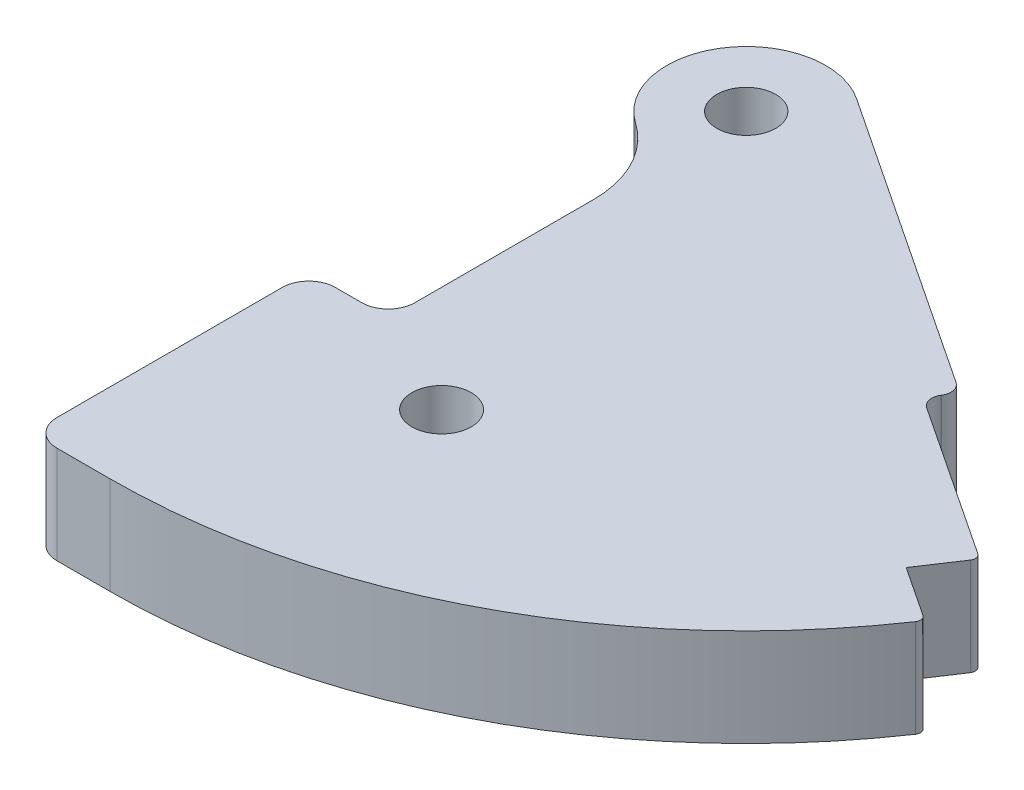
SolidWorks part; units mm, degrees
ref_plane "Front Plane" through (0, 0, 0) normal (0, 0, 1) x (1, 0, 0)
ref_plane "Top Plane" through (0, 0, 0) normal (0, 1, 0) x (1, 0, 0)
ref_plane "Right Plane" through (0, 0, 0) normal (1, 0, 0) x (0, 0, -1)
sketch "Sketch1" plane through (0, 0, 0) normal (0, 1, 0) x (1, 0, 0)
  line L0 (0, -4.7625) -> (0, -21.4312)
  line L1 (0, 0) -> (31.75, -21.0606) construction
  line L2 (0, 0) -> (31.75, 0) construction
  line L3 (31.75, 0) -> (31.75, -38.2189) construction
  line L4 (2.6326, 3.9688) -> (20.9847, -8.2046)
  line L5 (-4.7625, 0) -> (-4.7625, -37.8012) construction
  line L6 (0, -21.4312) -> (-4.7625, -21.4312)
  line L7 (-4.7625, -21.4312) -> (-4.7625, -38.1)
  line L8 (0, -38.1) -> (-4.7625, -38.1)
  line L9 (28.4427, -18.8668) -> (30.1978, -16.2209)
  line L10 (20.9847, -8.2046) -> (20.1309, -9.5433)
  line L11 (28.4427, -18.8668) -> (31.75, -21.0606)
  line L12 (30.1978, -16.2209) -> (20.1309, -9.5433)
  arc A0 (0, -38.1) -> (31.75, -21.0606) centre (0, 0) ccw
  circle A1 centre (0, 0) radius 1.7653
  arc A2 (4.7625, 0) -> (0, -4.7625) centre (0, 0) ccw
  arc A3 (4.7625, 0) -> (0, -4.7625) centre (0, 0) cw
  circle A4 centre (6.35, -24.5934) radius 1.778
  dimension "D2" = 76.2
  dimension "D3" = 3.5306
  dimension "D4" = 9.525
  dimension "D9" = 3.556
  dimension "D1" = 31.75
  dimension "D5" = 16.6687
  dimension "D6" = 16.6688
  dimension "D7" = 3.9688
  dimension "D10" = 6.35
  dimension "D11" = 25.4
  dimension "D12" = 3.175
extrude "Boss-Extrude1" add sketch "Sketch1" along normal blind 5.842
fillet "Fillet3" radius 1.5875 3 edges at (-4.7625, 2.921, 38.1) (-4.7625, 2.921, 21.4312) (0, 2.921, 21.4312)
fillet "Fillet6" radius 6.35 1 edges at (0, 2.921, 4.7625)
fillet "Fillet7" radius 0.3969 2 edges at (31.75, 2.921, 21.0606) (30.1978, 2.921, 16.2209)
fillet "Fillet9" radius 0.7937 2 edges at (20.9847, 2.921, 8.2046) (20.1309, 2.921, 9.5433)
